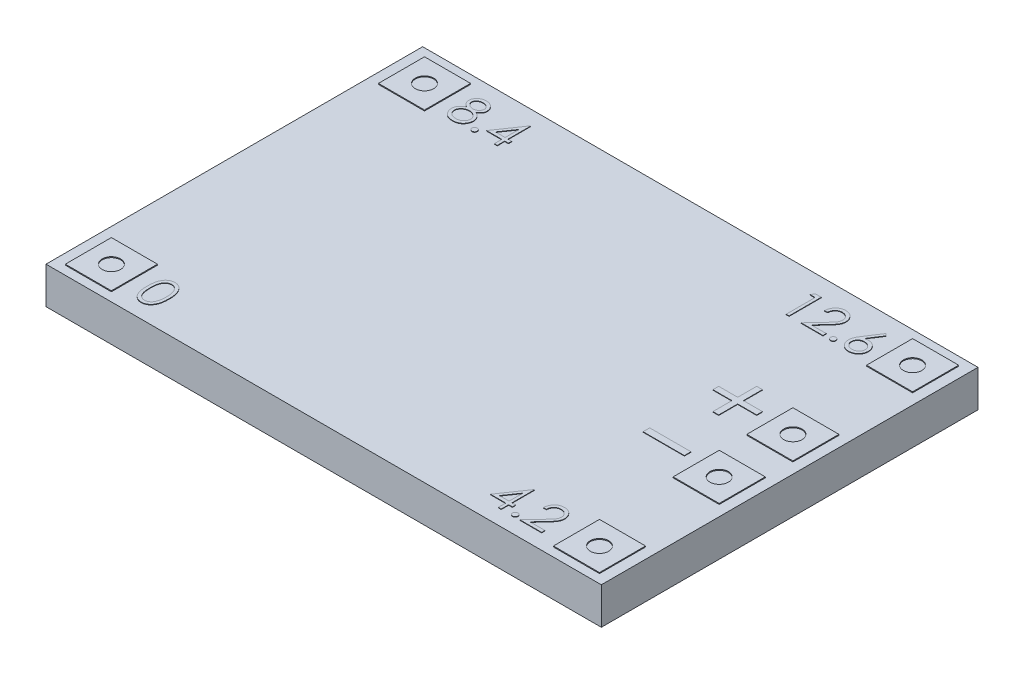
SolidWorks part; units mm, degrees
ref_plane "Спереди" through (0, 0, 0) normal (0, 0, 1) x (1, 0, 0)
ref_plane "Сверху" through (0, 0, 0) normal (0, 1, 0) x (1, 0, 0)
ref_plane "Справа" through (0, 0, 0) normal (1, 0, 0) x (0, 0, -1)
sketch "Эскиз1" plane through (0, 0, 0) normal (0, 1, 0) x (1, 0, 0)
  line L1 (30.15, -20.45) -> (-30.15, -20.45)
  line L2 (30.15, -20.45) -> (30.15, 20.45)
  line L3 (30.15, 20.45) -> (-30.15, 20.45)
  line L4 (-30.15, -20.45) -> (-30.15, 20.45)
  line L5 (30.15, -20.45) -> (-30.15, 20.45) construction
  line L6 (30.15, 20.45) -> (-30.15, -20.45) construction
  point P0 (0, 0)
  point P5 (0, 0)
  dimension "D1" = 40.9
  dimension "D2" = 60.3
extrude "Бобышка-Вытянуть1" add sketch "Эскиз1" along normal blind 4
sketch "Эскиз2" plane through (0, 4, 0) normal (0, 1, 0) x (1, 0, 0)
  line L0 (0, 6.7905) -> (0, -5.6858) construction
  line L5 (-24, 14.5) -> (-29, 19.5) construction
  line L6 (-24, 19.5) -> (-29, 14.5) construction
  line L7 (-24, -19.5) -> (-29, -19.5)
  line L8 (-24, -19.5) -> (-24, -14.5)
  line L9 (-24, -14.5) -> (-29, -14.5)
  line L10 (-29, -19.5) -> (-29, -14.5)
  line L11 (-24, -19.5) -> (-29, -14.5) construction
  line L12 (-24, -14.5) -> (-29, -19.5) construction
  line L17 (-29, 19.5) -> (-29, 14.5)
  line L18 (-24, 14.5) -> (-29, 14.5)
  line L23 (-24, 19.5) -> (-24, 14.5)
  line L24 (-24, 19.5) -> (-29, 19.5)
  line L25 (-22.3533, 0) -> (10.7868, 0) construction
  line L26 (24, -14.5) -> (29, -19.5) construction
  line L27 (24, -19.5) -> (29, -14.5) construction
  line L28 (24, 19.5) -> (29, 14.5) construction
  line L29 (24, 14.5) -> (29, 19.5) construction
  line L30 (24, 19.5) -> (29, 19.5)
  line L31 (24, 19.5) -> (24, 14.5)
  line L32 (24, 14.5) -> (29, 14.5)
  line L33 (29, 19.5) -> (29, 14.5)
  line L34 (29, -19.5) -> (29, -14.5)
  line L35 (24, -14.5) -> (29, -14.5)
  line L36 (24, -19.5) -> (24, -14.5)
  line L37 (24, -19.5) -> (29, -19.5)
  line L38 (29, -6.5) -> (24, -1.5) construction
  line L39 (29, 1.5) -> (24, 1.5)
  line L40 (29, 1.5) -> (29, 6.5)
  line L41 (29, 6.5) -> (24, 6.5)
  line L42 (24, 1.5) -> (24, 6.5)
  line L43 (29, 1.5) -> (24, 6.5) construction
  line L44 (29, 6.5) -> (24, 1.5) construction
  line L45 (29, -1.5) -> (24, -6.5) construction
  line L46 (24, -1.5) -> (24, -6.5)
  line L47 (29, -6.5) -> (24, -6.5)
  line L48 (29, -1.5) -> (29, -6.5)
  line L49 (29, -1.5) -> (24, -1.5)
  circle A3 centre (-26.5, -17) radius 1
  circle A4 centre (-26.5, 17) radius 1
  circle A5 centre (26.5, 17) radius 1
  circle A6 centre (26.5, -17) radius 1
  circle A7 centre (26.5, 4) radius 1
  circle A8 centre (26.5, -4) radius 1
  point P5 (-26.5, -17)
  point P11 (-26.5, 17)
  point P24 (26.5, 17)
  point P25 (26.5, -17)
  point P33 (26.5, 4)
  point P42 (26.5, -4)
  dimension "D1" = 2
  dimension "D2" = 34
  dimension "D3" = 53
  dimension "D6" = 5
  dimension "D4" = 5
  dimension "D5" = 5
  dimension "D7" = 8
extrude "Бобышка-Вытянуть2" add sketch "Эскиз2" along normal blind 0.1 separate body
sketch "Эскиз3" plane through (0, 4, 0) normal (0, 1, 0) x (1, 0, 0)
  text T0 "+" font "Century Gothic" height 7
  text T1 "-" font "Century Gothic" height 7
  text T2 "12.6"
  text T3 "8.4"
  text T4 "0"
  text T5 "4.2\r\n"
  point P6 (14.0665, -11.2752)
extrude "Бобышка-Вытянуть3" add sketch "Эскиз3" along normal blind 0.05 separate body
